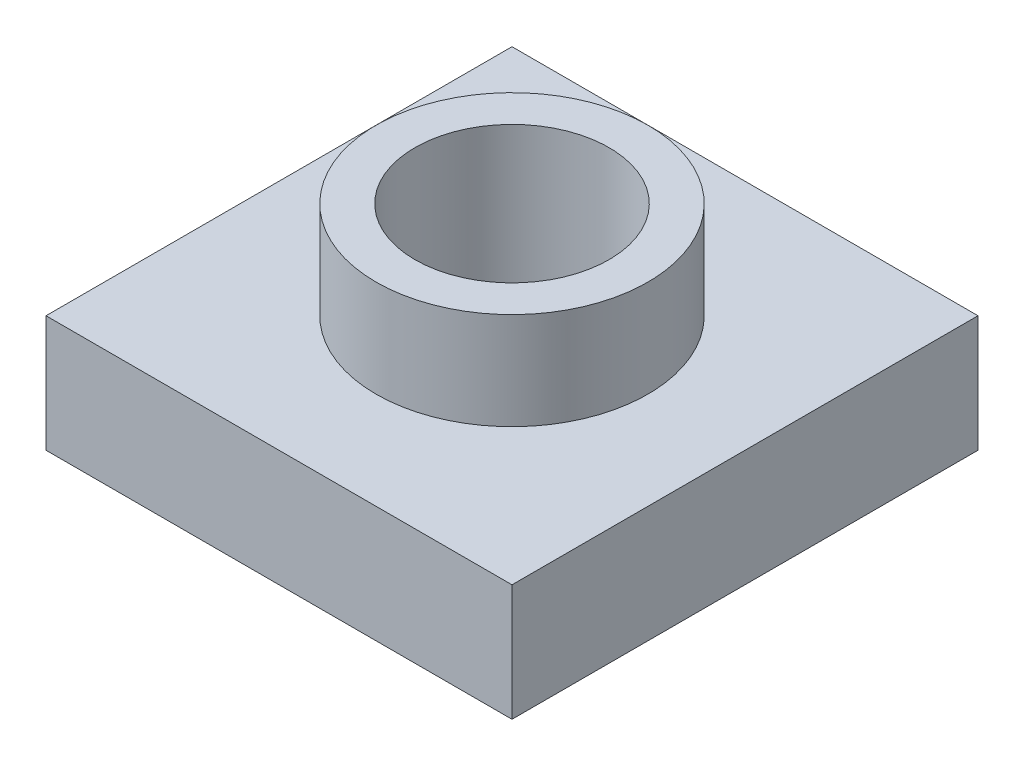
SolidWorks part; units mm, degrees
ref_plane "Plan de face" through (0, 0, 0) normal (0, 0, 1) x (1, 0, 0)
ref_plane "Plan de dessus" through (0, 0, 0) normal (0, 1, 0) x (1, 0, 0)
ref_plane "Plan de droite" through (0, 0, 0) normal (1, 0, 0) x (0, 0, -1)
sketch "Esquisse1" plane through (-22.8404, 0, 13.944) normal (0, 1, 0) x (1, 0, 0)
  line L1 (0, 113.2824) -> (120, 113.2824)
  line L2 (0, 113.2824) -> (0, -6.7176)
  line L3 (0, -6.7176) -> (120, -6.7176)
  line L4 (120, 113.2824) -> (120, -6.7176)
  dimension "D1" = 120
  dimension "D2" = 120
extrude "Boss.-Extru.1" add sketch "Esquisse1" along normal blind 30
sketch "Esquisse3" plane through (0, 30, 0) normal (0, 1, 0) x (1, 0, 0)
  line L0 (97.1596, 99.3384) -> (-22.8404, 99.3384) construction
  line L1 (97.1596, -20.6616) -> (97.1596, 99.3384) construction
  circle A0 centre (37.1596, 39.3384) radius 35
  point P4 (37.1596, 99.3384)
  dimension "D1" = 70
  dimension "D2" = 60
  dimension "D3" = 60
extrude "Boss.-Extru.2" add sketch "Esquisse3" along normal blind 25
sketch "Esquisse6" plane through (0, 55, 0) normal (0, 1, 0) x (1, 0, 0)
  circle A0 centre (37.1596, 39.3384) radius 25
  dimension "D1" = 50
extrude "Enlèv. mat.-Extru.2" cut sketch "Esquisse6" against normal through all
